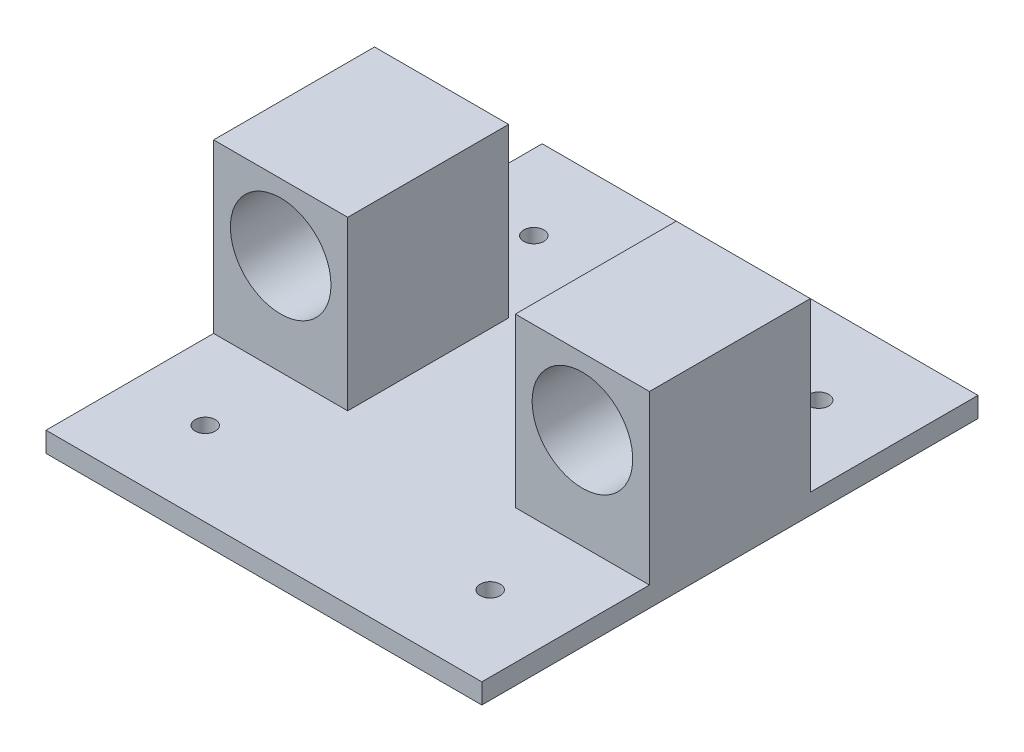
SolidWorks part; units mm, degrees
ref_plane "Front Plane" through (0, 0, 0) normal (0, 0, 1) x (1, 0, 0)
ref_plane "Top Plane" through (0, 0, 0) normal (0, 1, 0) x (1, 0, 0)
ref_plane "Right Plane" through (0, 0, 0) normal (1, 0, 0) x (0, 0, -1)
sketch "Sketch1" plane through (0, 0, 0) normal (0, 0, 1) x (1, 0, 0)
  line L0 (0, 0) -> (0, 39.6845) construction
  line L1 (32.5, 0) -> (-32.5, 0)
  line L2 (-32.5, 0) -> (-32.5, 28)
  line L3 (-32.5, 28) -> (-12.5, 28)
  line L4 (-12.5, 28) -> (-12.5, 3)
  line L5 (-12.5, 3) -> (12.5, 3)
  line L6 (12.5, 28) -> (12.5, 3)
  line L7 (32.5, 28) -> (12.5, 28)
  line L8 (32.5, 0) -> (32.5, 28)
  point P9 (0, 3)
  dimension "D1" = 25
  dimension "D2" = 3
  dimension "D3" = 65
  dimension "D4" = 25
extrude "Boss-Extrude1" add sketch "Sketch1" along normal mid plane 24
sketch "Sketch2" plane through (0, 0, 12) normal (0, 0, 1) x (1, 0, 0)
  line L0 (-22.5, 28) -> (-22.5, 0) construction
  line L1 (-12.5, 28) -> (-32.5, 28) construction
  line L2 (-32.5, 0) -> (32.5, 0) construction
  circle A0 centre (-22.5, 18) radius 7.5
  dimension "D1" = 15
  dimension "D2" = 10
extrude "Cut-Extrude1" cut sketch "Sketch2" against normal through all
mirror "Mirror1" about plane through (0, 0, 0) normal (1, 0, 0) of "Cut-Extrude1"
sketch "Sketch3" plane through (0, 0, 12) normal (0, 0, 1) x (1, 0, 0)
  line L0 (-32.5, 0) -> (32.5, 0)
  line L1 (32.5, 0) -> (32.5, 3)
  line L2 (32.5, 0) -> (32.5, 28) construction
  line L3 (32.5, 3) -> (-32.5, 3)
  line L4 (-32.5, 28) -> (-32.5, 0) construction
  line L5 (-32.5, 3) -> (-32.5, 0)
  dimension "D1" = 3
extrude "Boss-Extrude2" add sketch "Sketch3" along normal blind 25
sketch "Sketch4" plane through (0, 3, 0) normal (0, 1, 0) x (1, 0, 0)
  line L0 (-32.5, -24.5) -> (32.5, -24.5) construction
  line L1 (-32.5, -37) -> (-32.5, -12) construction
  line L2 (32.5, -37) -> (32.5, -12) construction
  line L3 (0, -37) -> (0, 0) construction
  line L4 (32.5, -37) -> (-32.5, -37) construction
  circle A0 centre (-21.25, -24.5) radius 1.5
  circle A1 centre (21.25, -24.5) radius 1.5
  dimension "D1" = 3
  dimension "D2" = 42.5
extrude "Cut-Extrude2" cut sketch "Sketch4" against normal through all both and the other way through all
mirror "Mirror2" about plane through (0, 0, 0) normal (0, 0, 1) of "Cut-Extrude2", "Boss-Extrude2"
